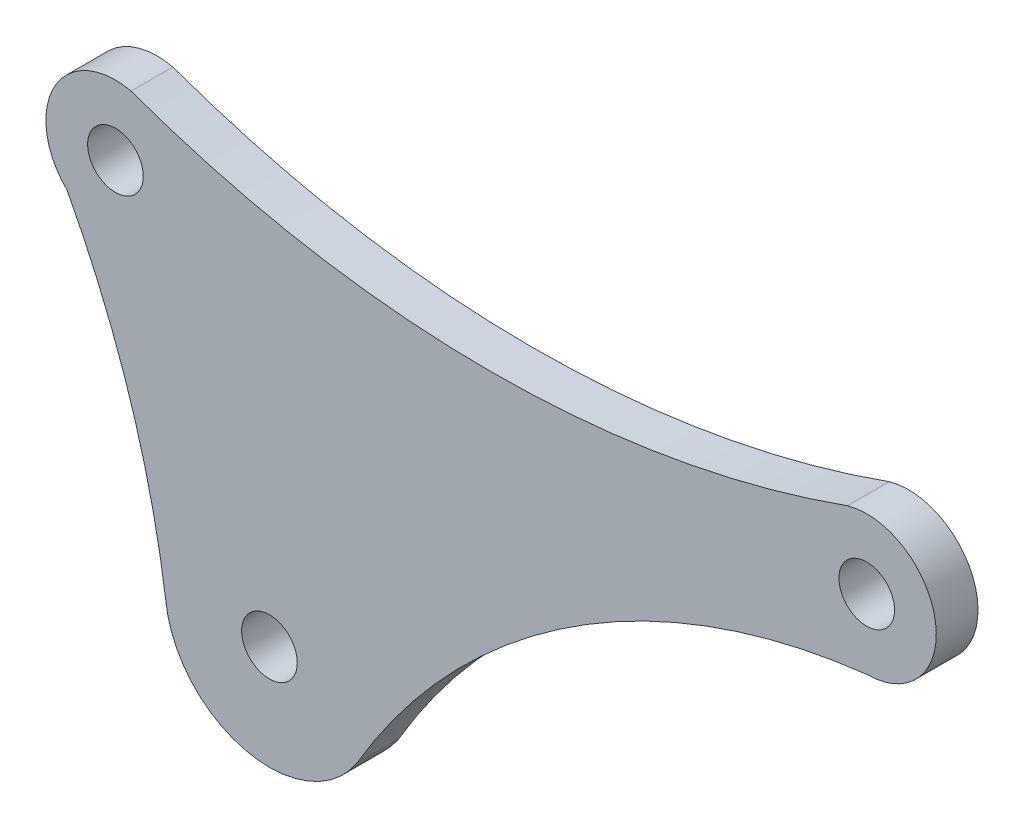
SolidWorks part; units mm, degrees
ref_plane "前视基准面" through (0, 0, 0) normal (0, 0, 1) x (1, 0, 0)
ref_plane "上视基准面" through (0, 0, 0) normal (0, 1, 0) x (1, 0, 0)
ref_plane "右视基准面" through (0, 0, 0) normal (1, 0, 0) x (0, 0, -1)
sketch "草图1" plane through (0, 0, 0) normal (0, 0, 1) x (1, 0, 0)
  line L0 (55, 0) -> (-55, 0) construction
  arc A0 (2.1903, 4.4947) -> (-3.472, -3.5979) centre (0, 0) ccw
  arc A1 (54, -5) -> (52.0513, 4.6046) centre (54, 0) ccw
  arc A2 (3.6105, -25.5283) -> (17.6777, -28.2981) centre (11.07, -24.75) ccw
  arc A3 (1.1221, 4.8725) -> (52.6126, 4.8036) centre (26.9628, 76.2474) ccw
  arc A4 (-3.472, -3.5979) -> (3.6105, -25.5283) centre (-61.9841, -34.6035) cw
  arc A5 (17.3425, -28.8616) -> (54, -5) centre (59.5137, -53.5588) cw
  circle A6 centre (0, 0) radius 2
  circle A7 centre (54, 0) radius 2
  circle A8 centre (11.07, -24.75) radius 2
extrude "凸台-拉伸1" add sketch "草图1" along normal mid plane 3 contours A2 A5 A1 A3 A0 A4 A8 A7 A6
